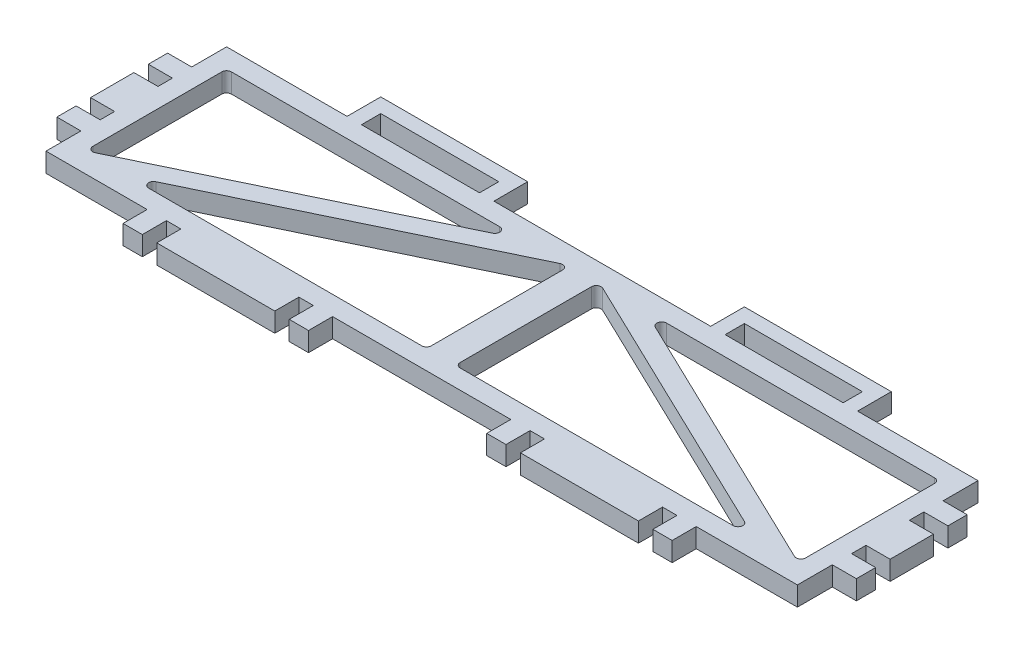
SolidWorks part; units mm, degrees
ref_plane "Front Plane" through (0, 0, 0) normal (0, 0, 1) x (1, 0, 0)
ref_plane "Top Plane" through (0, 0, 0) normal (0, 1, 0) x (1, 0, 0)
ref_plane "Right Plane" through (0, 0, 0) normal (1, 0, 0) x (0, 0, -1)
sketch "Sketch1" plane through (0, 0, 0) normal (0, 1, 0) x (1, 0, 0)
  line L0 (0, 18.75) -> (0, -18.75) construction
  line L1 (-78, 18.75) -> (78, 18.75)
  line L2 (-78, 18.75) -> (-78, -18.75)
  line L3 (-78, -18.75) -> (78, -18.75)
  line L4 (78, 18.75) -> (78, -18.75)
  line L5 (-50, -18.75) -> (-25.5, -18.75)
  line L6 (-50, -18.75) -> (-50, -23.75)
  line L7 (-50, -23.75) -> (-25.5, -23.75)
  line L8 (-25.5, -18.75) -> (-25.5, -23.75)
  line L9 (25.5, -18.75) -> (50, -18.75)
  line L10 (25.5, -18.75) -> (25.5, -23.75)
  line L11 (25.5, -23.75) -> (50, -23.75)
  line L12 (50, -18.75) -> (50, -23.75)
  line L13 (78, 4.5) -> (83, 4.5)
  line L14 (78, 4.5) -> (78, -4.5)
  line L15 (78, -4.5) -> (83, -4.5)
  line L16 (83, 4.5) -> (83, -4.5)
  line L17 (-78, 0) -> (78, 0) construction
  line L26 (12.9358, 14.75) -> (74, -14.6078)
  line L27 (74, -14.6078) -> (74, 14.75)
  line L28 (74, 14.75) -> (12.9358, 14.75)
  line L29 (3, 15.0886) -> (65.0642, -14.75)
  line L30 (65.0642, -14.75) -> (3, -14.75)
  line L31 (3, -14.75) -> (3, 15.0886)
  line L32 (-74, -14.6078) -> (-74, 14.75)
  line L33 (-12.9358, 14.75) -> (-74, -14.6078)
  line L34 (-74, 14.75) -> (-12.9358, 14.75)
  line L35 (-78, -4.5) -> (-83, -4.5)
  line L36 (-83, 4.5) -> (-83, -4.5)
  line L37 (-78, 4.5) -> (-83, 4.5)
  line L38 (-78, 4.5) -> (-78, -4.5)
  line L39 (-3, -14.75) -> (-3, 15.0886)
  line L40 (-65.0642, -14.75) -> (-3, -14.75)
  line L41 (-3, 15.0886) -> (-65.0642, -14.75)
  line L42 (22.5, -23.75) -> (18.5, -23.75)
  line L47 (22.5, 18.75) -> (53, 18.75)
  line L48 (22.5, 18.75) -> (22.5, 25.75)
  line L49 (22.5, 25.75) -> (53, 25.75)
  line L50 (53, 18.75) -> (53, 25.75)
  line L51 (-22.5, 18.75) -> (-53, 18.75)
  line L52 (-22.5, 18.75) -> (-22.5, 25.75)
  line L53 (-22.5, 25.75) -> (-53, 25.75)
  line L54 (-53, 18.75) -> (-53, 25.75)
  line L55 (-50, 18.75) -> (-25.5, 18.75)
  line L56 (-50, 18.75) -> (-50, 22.75)
  line L57 (-50, 22.75) -> (-25.5, 22.75)
  line L58 (-25.5, 18.75) -> (-25.5, 22.75)
  line L59 (25.5, 18.75) -> (50, 18.75)
  line L60 (25.5, 18.75) -> (25.5, 22.75)
  line L61 (25.5, 22.75) -> (50, 22.75)
  line L62 (50, 18.75) -> (50, 22.75)
  line L71 (-78, 7.5) -> (-83, 7.5)
  line L72 (-78, 7.5) -> (-78, 11.5)
  line L73 (-78, 11.5) -> (-83, 11.5)
  line L74 (-83, 7.5) -> (-83, 11.5)
  line L75 (-78, -7.5) -> (-83, -7.5)
  line L76 (-78, -7.5) -> (-78, -11.5)
  line L77 (-78, -11.5) -> (-83, -11.5)
  line L78 (-83, -7.5) -> (-83, -11.5)
  line L79 (-22.5, -18.75) -> (-18.5, -18.75)
  line L80 (-22.5, -18.75) -> (-22.5, -23.75)
  line L81 (-22.5, -23.75) -> (-18.5, -23.75)
  line L82 (-18.5, -18.75) -> (-18.5, -23.75)
  line L83 (-53, -18.75) -> (-57, -18.75)
  line L84 (-53, -18.75) -> (-53, -23.75)
  line L85 (-53, -23.75) -> (-57, -23.75)
  line L86 (-57, -18.75) -> (-57, -23.75)
  line L87 (18.5, -18.75) -> (18.5, -23.75)
  line L88 (22.5, -18.75) -> (18.5, -18.75)
  line L89 (22.5, -18.75) -> (22.5, -23.75)
  line L90 (53, -23.75) -> (57, -23.75)
  line L91 (57, -18.75) -> (57, -23.75)
  line L92 (53, -18.75) -> (57, -18.75)
  line L93 (53, -18.75) -> (53, -23.75)
  line L94 (78, -11.5) -> (83, -11.5)
  line L95 (83, -7.5) -> (83, -11.5)
  line L96 (78, -7.5) -> (83, -7.5)
  line L97 (78, -7.5) -> (78, -11.5)
  line L98 (78, 11.5) -> (83, 11.5)
  line L99 (83, 7.5) -> (83, 11.5)
  line L100 (78, 7.5) -> (83, 7.5)
  line L101 (78, 7.5) -> (78, 11.5)
  point P4 (0, 18.75)
  point P6 (-78, 0)
  point P19 (83, 0)
  point P20 (78, 0)
  point P57 (-37.75, 22.75)
  point P58 (-37.75, -23.75)
  point P59 (37.75, 22.75)
  point P60 (37.75, -23.75)
  point P61 (-37.75, 25.75)
  point P62 (37.75, 25.75)
  dimension "D1" = 156
  dimension "D2" = 37.5
  dimension "D3" = 28
  dimension "D4" = 24.5
  dimension "D5" = 28
  dimension "D6" = 24.5
  dimension "D7" = 5
  dimension "D8" = 9
  dimension "D9" = 5
  dimension "D10" = 4
  dimension "D11" = 4
  dimension "D12" = 4
  dimension "D13" = 3
  dimension "D14" = 4
  dimension "D15" = 2
  dimension "D16" = 2
  dimension "D17" = 3
  dimension "D18" = 3
  dimension "D19" = 24.5
  dimension "D20" = 3
  dimension "D21" = 7
  dimension "D22" = 3
  dimension "D23" = 3
  dimension "D24" = 4
  dimension "D25" = 3
  dimension "D26" = 4
  dimension "D27" = 3
extrude "Boss-Extrude1" add sketch "Sketch1" along normal blind 4 contours L4 L1 L47 L51 L2 L3 L41 L39 L40 L28 L27 L26 L30 L31 L29 L32 L34 | L62 L1 L50 L49 L48 L60 L61 | L58 L1 L52 L53 L54 L56 L57 | L89 L3 L87 L42 | L12 L3 L10 L11 | L3 L93 L90 L91 | L96 L4 L94 L95 | L16 L13 L4 L15 | L4 L100 L99 L98 | L82 L3 L80 L81 | L8 L3 L6 L7 | L3 L86 L85 L84 | L75 L78 L77 L2 | L2 L37 L36 L35 | L74 L71 L2 L73
fillet "Fillet1" radius 1 12 edges at (74, 2, 14.6078) (12.9358, 2, -14.75) (3, 2, -15.0886) (65.0642, 2, 14.75) (-3, 2, 14.75) (3, 2, 14.75) (-65.0642, 2, 14.75) (-12.9358, 2, -14.75) (-74, 2, 14.6078) (-74, 2, -14.75) (-3, 2, -15.0886) (74, 2, -14.75)
